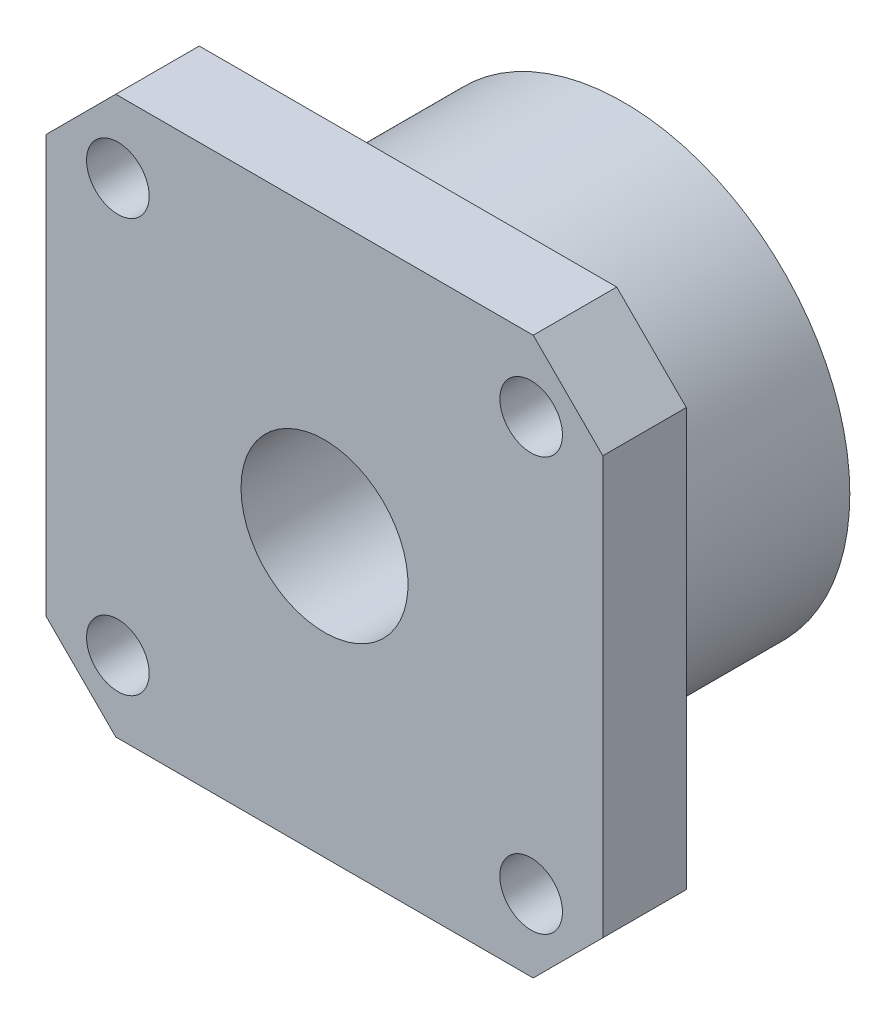
SolidWorks part; units mm, degrees
ref_plane "前视基准面" through (0, 0, 0) normal (0, 0, 1) x (1, 0, 0)
ref_plane "上视基准面" through (0, 0, 0) normal (0, 1, 0) x (1, 0, 0)
ref_plane "右视基准面" through (0, 0, 0) normal (1, 0, 0) x (0, 0, -1)
sketch "草图1" plane through (0, 0, 0) normal (0, 0, 1) x (1, 0, 0)
  line L1 (20, -20) -> (-20, -20)
  line L2 (20, -20) -> (20, 20)
  line L3 (20, 20) -> (-20, 20)
  line L4 (-20, -20) -> (-20, 20)
  line L5 (20, -20) -> (-20, 20) construction
  line L6 (20, 20) -> (-20, -20) construction
  circle A0 centre (-14.8492, 14.8492) radius 2.25
  circle A2 centre (14.8492, 14.8492) radius 2.25
  circle A3 centre (14.8492, -14.8492) radius 2.25
  circle A4 centre (-14.8492, -14.8492) radius 2.25
  point P0 (0, 0)
  dimension "D2" = 4.5
  dimension "D3" = 21
  dimension "D1" = 40
  dimension "D4" = 4
extrude "凸台-拉伸1" add sketch "草图1" along normal blind 6
chamfer "倒角1" distance 5 angle 45 4 edges at (-20, -20, 3) (20, -20, 3) (20, 20, 3) (-20, 20, 3)
sketch "草图2" plane through (0, 0, 0) normal (0, 0, -1) x (-1, 0, 0)
  circle A0 centre (0, 0) radius 16.25
  circle A1 centre (0, 0) radius 6
  dimension "D1" = 32.5
  dimension "D2" = 12
extrude "凸台-拉伸2" add sketch "草图2" along normal blind 15.5
sketch "草图3" plane through (0, 0, 0) normal (0, 0, -1) x (-1, 0, 0)
  circle A1 centre (0, 0) radius 6
  circle A4 centre (0, 0) radius 6
  dimension "D1" = 0
extrude "切除-拉伸1" cut sketch "草图3" against normal through all
